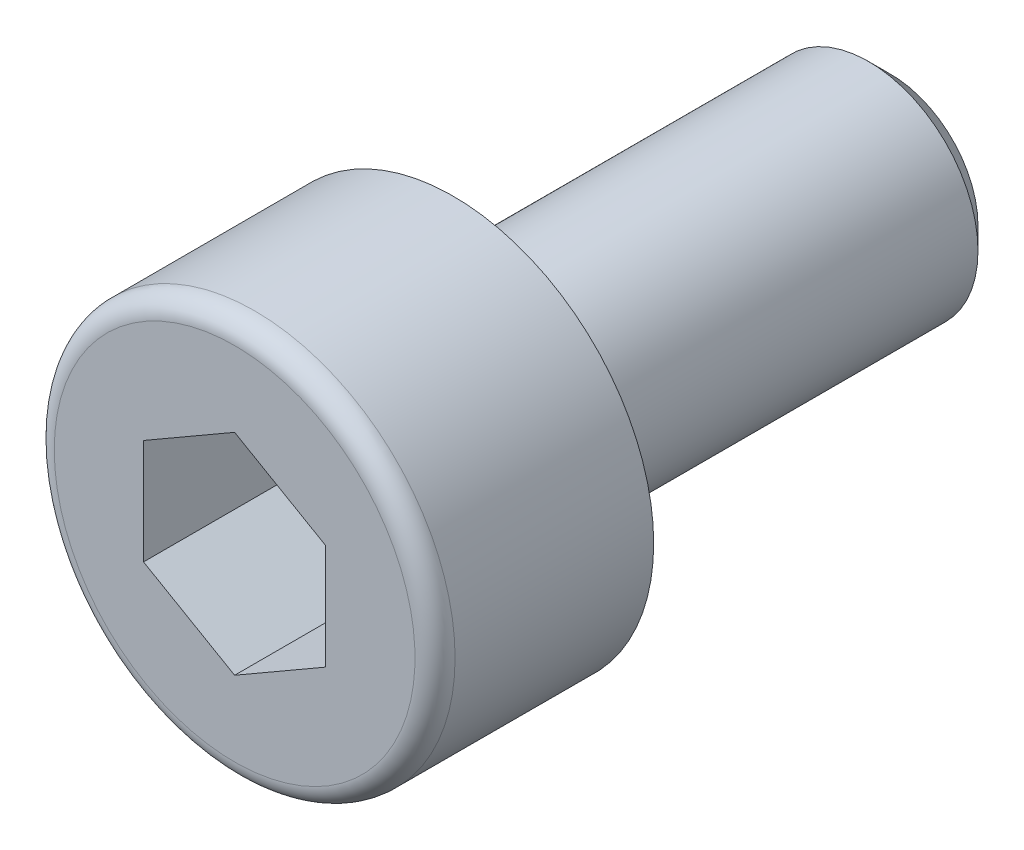
SolidWorks part; units mm, degrees
material "普通碳钢"
ref_plane "前视基准面" through (0, 0, 0) normal (0, 0, 1) x (1, 0, 0)
ref_plane "上视基准面" through (0, 0, 0) normal (0, 1, 0) x (1, 0, 0)
ref_plane "右视基准面" through (0, 0, 0) normal (1, 0, 0) x (0, 0, -1)
sketch "草图1" plane through (0, 0, 0) normal (1, 0, 0) x (0, 0, -1)
  line L0 (-3, 0) -> (30, 0) construction
  line L1 (-3, 0) -> (-3, 2.75)
  line L2 (-3, 2.75) -> (0, 2.75)
  line L3 (0, 2.75) -> (0, 1.5)
  line L4 (0, 1.5) -> (30, 1.5)
  line L5 (30, 1.5) -> (30, 0)
  point P3 (12, 1.5)
  dimension "A" = 5.5
  dimension "E" = 3
  dimension "L" = 30
  dimension "(e)" = 18
  dimension "M" = 3
sketch "草图2" plane through (0, 0, 0) normal (0, 0, 1) x (1, 0, 0)
  line L1 (0, 1.4434) -> (-1.25, 0.7217)
  line L2 (-1.25, 0.7217) -> (-1.25, -0.7217)
  line L3 (-1.25, -0.7217) -> (0, -1.4434)
  line L4 (0, -1.4434) -> (1.25, -0.7217)
  line L5 (1.25, -0.7217) -> (1.25, 0.7217)
  line L6 (1.25, 0.7217) -> (0, 1.4434)
  circle A0 centre (0, 0) radius 1.25 construction
  dimension "B" = 2.5
sketch "草图3" plane through (0, 0, 0) normal (1, 0, 0) x (0, 0, -1)
  line L0 (-3, 0) -> (-3, 2.75) construction
  line L1 (-3, 2.75) -> (0, 2.75) construction
  line L3 (0, 2.75) -> (0, 1.5) construction
  line L6 (-3, 0) -> (-3, 2.75)
  line L7 (-3, 2.75) -> (0, 2.75)
  line L8 (0, 1.5) -> (6, 1.5)
  line L9 (0, 2.75) -> (0, 1.5)
  line L10 (-3, 0) -> (6, 0)
  line L11 (6, 1.5) -> (6, 0)
  dimension "D1" = 6
revolve "旋转1" add sketch "草图3" angle 360 about L10
cosmetic thread "装饰螺纹线1" parameters "D2"=2.459
sketch "草图4" plane through (0, 0, 3) normal (0, 0, 1) x (1, 0, 0)
  line L0 (0, 1.4434) -> (-1.25, 0.7217) construction
  line L1 (-1.25, 0.7217) -> (-1.25, -0.7217) construction
  line L2 (-1.25, -0.7217) -> (0, -1.4434) construction
  line L3 (0, -1.4434) -> (1.25, -0.7217) construction
  line L4 (1.25, -0.7217) -> (1.25, 0.7217) construction
  line L5 (1.25, 0.7217) -> (0, 1.4434) construction
  line L6 (0, 1.4434) -> (-1.25, 0.7217)
  line L7 (-1.25, 0.7217) -> (-1.25, -0.7217)
  line L8 (-1.25, -0.7217) -> (0, -1.4434)
  line L9 (0, -1.4434) -> (1.25, -0.7217)
  line L10 (1.25, -0.7217) -> (1.25, 0.7217)
  line L11 (1.25, 0.7217) -> (0, 1.4434)
extrude "切除-拉伸1" cut sketch "草图4" against normal blind 1.925
fillet "圆角1" radius 0.275 1 edges at (2.75, 0, 3)
chamfer "倒角1" distance 0.3 angle 45 1 edges at (1.5, 0, -6)
